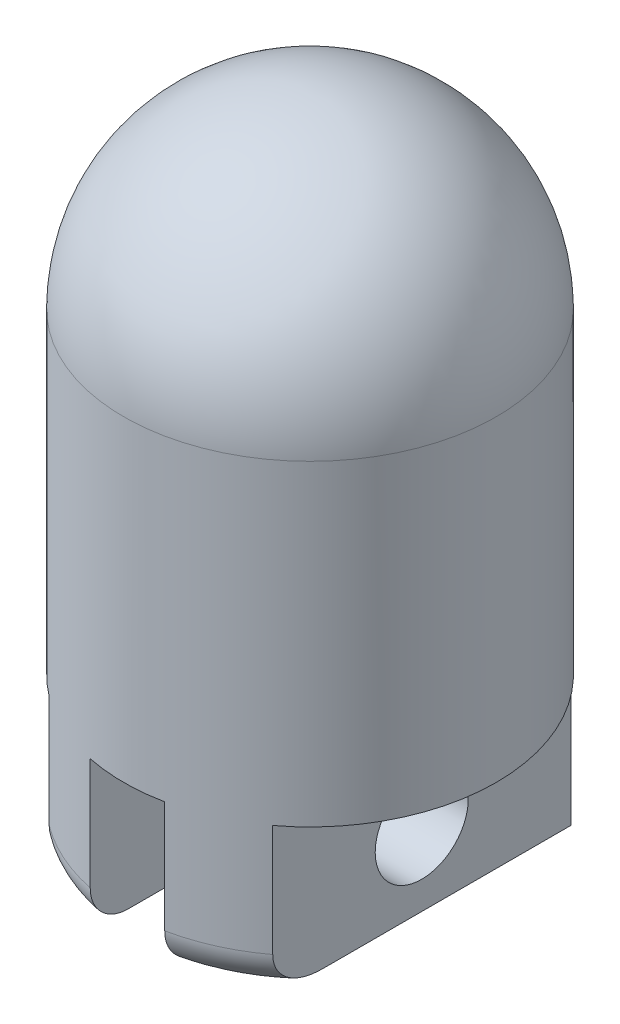
SolidWorks part; units mm, degrees
ref_plane "Front Plane" through (0, 0, 0) normal (0, 0, 1) x (1, 0, 0)
ref_plane "Top Plane" through (0, 0, 0) normal (0, 1, 0) x (1, 0, 0)
ref_plane "Right Plane" through (0, 0, 0) normal (1, 0, 0) x (0, 0, -1)
sketch "Sketch1" plane through (0, 0, 0) normal (0, 0, 1) x (1, 0, 0)
  line L0 (0, 0) -> (0, 5.6026)
  line L1 (0, 0) -> (-12.7, 0)
  line L2 (-12.7, 0) -> (-12.7, 31.75)
  line L6 (0, 5.6026) -> (-2.54, 5.6026)
  line L7 (-2.54, 22.86) -> (-2.54, 5.6026)
  line L8 (0, 40.9957) -> (0, 44.45)
  arc A0 (0, 44.45) -> (-12.7, 31.75) centre (0, 31.75) ccw
  arc A1 (-2.54, 22.86) -> (0, 40.9957) centre (0, 31.75) cw
  dimension "D3" = 25.4
  dimension "D1" = 44.45
  dimension "D2" = 12.7
  dimension "D4" = 2.54
revolve "Revolve1" add sketch "Sketch1" angle 360 about L0
sketch "Sketch2" plane through (0, 0, 0) normal (0, -1, 0) x (1, 0, 0)
  line L0 (-2.54, 12.4434) -> (-2.54, -12.4434)
  line L1 (-7.62, 10.16) -> (-7.62, -10.16)
  line L2 (2.54, 12.4434) -> (2.54, -12.4434)
  line L3 (7.62, 10.16) -> (7.62, -10.16)
  circle A0 centre (0, 0) radius 12.7 construction
  arc A1 (-7.62, 10.16) -> (-7.62, -10.16) centre (0, 0) ccw
  arc A2 (-2.54, -12.4434) -> (2.54, -12.4434) centre (0, 0) ccw
  arc A3 (7.62, -10.16) -> (7.62, 10.16) centre (0, 0) ccw
  arc A4 (2.54, 12.4434) -> (-2.54, 12.4434) centre (0, 0) ccw
  dimension "D1" = 2.54
  dimension "D2" = 5.08
  dimension "D3" = 2.54
  dimension "D4" = 5.08
extrude "Cut-Extrude1" cut sketch "Sketch2" against normal blind 10.16
sketch "Sketch3" plane through (-7.62, 0, 0) normal (-1, 0, 0) x (0, 0, 1)
  line L0 (0, -13.97) -> (0, 13.97) construction
  line L1 (-10.16, 0) -> (10.16, 0) construction
  circle A0 centre (0, 5.08) radius 3.175
  dimension "D2" = 6.35
  dimension "D1" = 5.08
extrude "Cut-Extrude2" cut sketch "Sketch3" against normal through all
fillet "Fillet1" radius 2.54 2 edges at (-5.2067, 0, 11.5836) (5.2067, 0, 11.5836)
